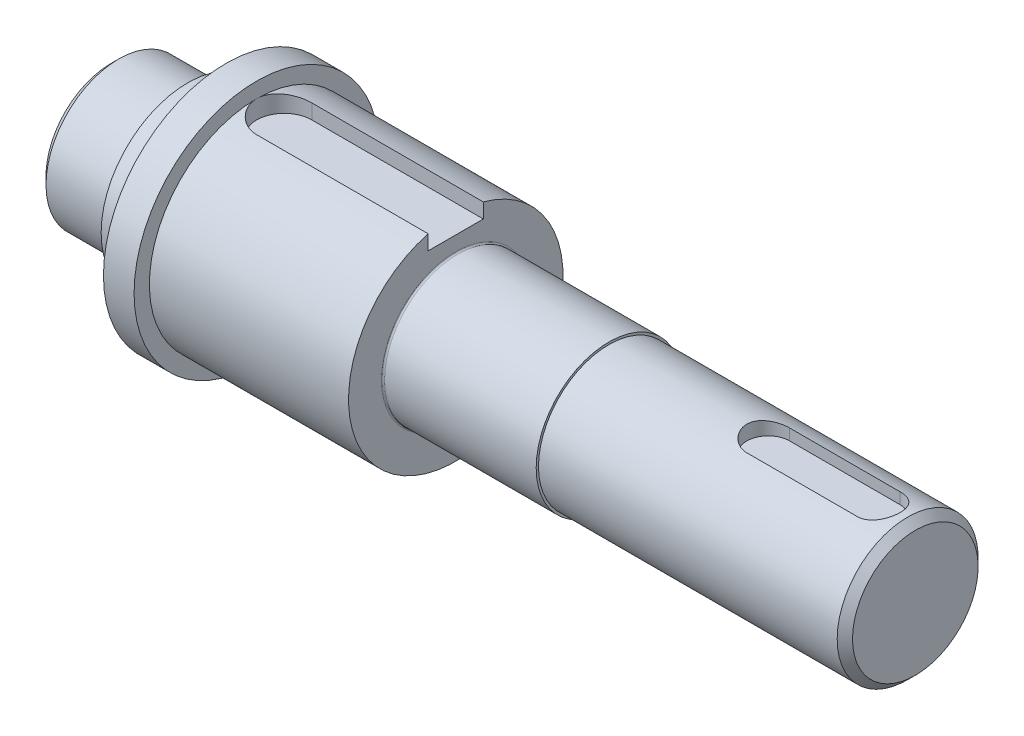
SolidWorks part; units mm, degrees
ref_plane "前视" through (0, 0, 0) normal (0, 0, 1) x (1, 0, 0)
ref_plane "上视" through (0, 0, 0) normal (0, 1, 0) x (1, 0, 0)
ref_plane "右视" through (0, 0, 0) normal (1, 0, 0) x (0, 0, -1)
sketch "草图1" plane through (0, 0, 0) normal (0, 0, 1) x (1, 0, 0)
  line L0 (0, 0) -> (548.0896, 0) construction
  line L1 (0, 0) -> (0, 47.5)
  line L2 (0, 47.5) -> (50, 47.5)
  line L3 (50, 47.5) -> (50, 56.5)
  line L4 (50, 56.5) -> (75, 56.5)
  line L5 (75, 56.5) -> (75, 80)
  line L6 (75, 80) -> (95, 80)
  line L7 (95, 80) -> (95, 70)
  line L8 (95, 70) -> (225, 70)
  line L9 (225, 70) -> (225, 47.5)
  line L10 (225, 47.5) -> (325, 47.5)
  line L11 (325, 47.5) -> (325, 46)
  line L12 (325, 46) -> (525, 46)
  line L13 (525, 46) -> (525, 0)
  line L14 (525, 0) -> (0, 0)
  dimension "D1" = 47.5
  dimension "D2" = 50
  dimension "D3" = 200
  dimension "D4" = 525
  dimension "D5" = 20
  dimension "D6" = 130
  dimension "D7" = 100
  dimension "D8" = 56.5
  dimension "D9" = 80
  dimension "D10" = 70
  dimension "D12" = 46
revolve "旋转1" add sketch "草图1" angle 360 about L0
ref_plane "基准面1" through (0, 70, 0) normal (0, 1, 0) x (-1, 0, 0)
sketch "草图2" plane through (0, 70, 0) normal (0, 1, 0) x (-1, 0, 0)
  line L0 (-386.0361, 0) -> (169.2594, 0) construction
  line L1 (-225, 18) -> (-225, -18)
  line L3 (-225, 70) -> (-225, -70) construction
  line L4 (-225, -18) -> (-113, -18)
  line L5 (-225, 18) -> (-113, 18)
  arc A0 (-113, 18) -> (-113, -18) centre (-113, 0) cw
  dimension "D1" = 112
  dimension "D2" = 36
  dimension "D3" = 18
extrude "切除-拉伸1" cut sketch "草图2" against normal blind 12
sketch "草图3" plane through (0, 0, 0) normal (0, 1, 0) x (-1, 0, 0)
  line L1 (-429, 14) -> (-501, 14)
  line L2 (-429, -14) -> (-501, -14)
  line L4 (-525, 46) -> (-525, -46) construction
  arc A0 (-429, 14) -> (-429, -14) centre (-429, 0) cw
  arc A1 (-501, 14) -> (-501, -14) centre (-501, 0) ccw
  dimension "D1" = 100
  dimension "D2" = 10
  dimension "D3" = 28
extrude "切除-拉伸2" cut sketch "草图3" along normal through all from offset 36.5
chamfer "倒角1" distance 5 angle 45 2 edges at (525, 0, 46) (0, 0, 47.5)
fillet "圆角1" radius 1 1 edges at (225, 0, 47.5)
